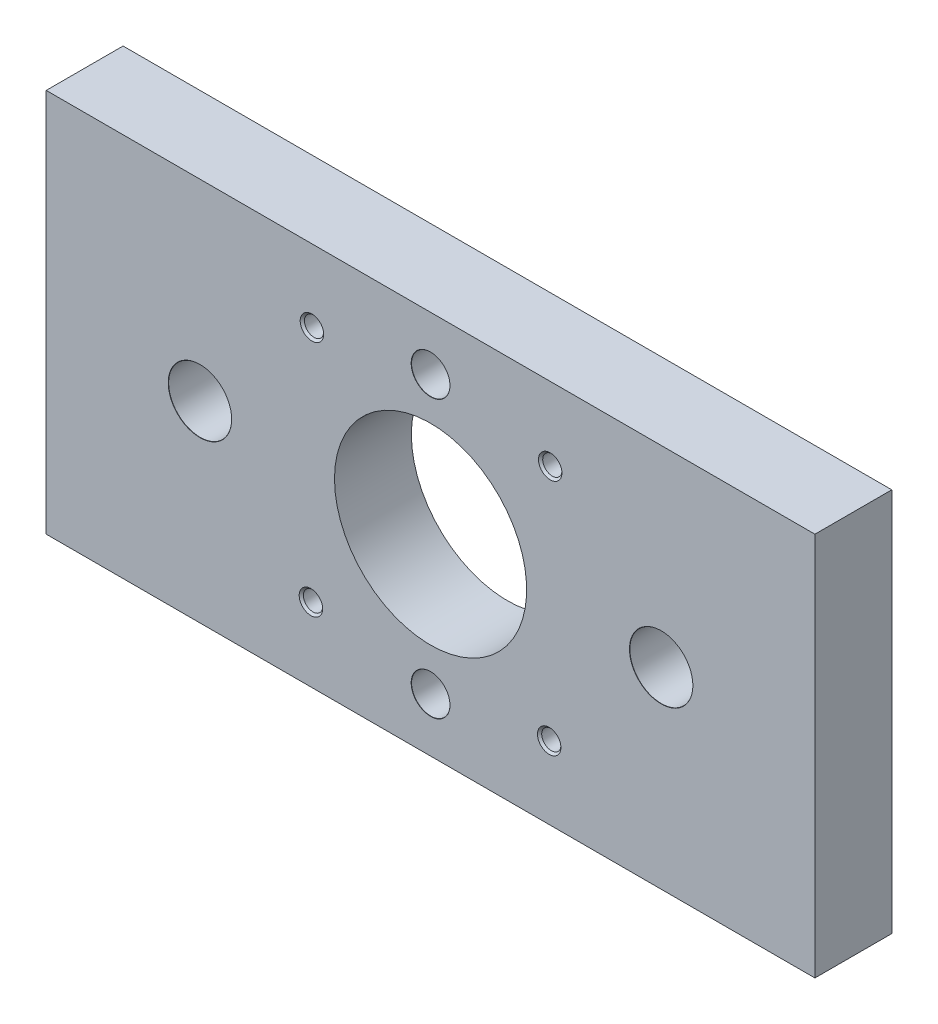
SolidWorks part; units mm, degrees
ref_plane "前视基准面" through (0, 0, 0) normal (0, 0, 1) x (1, 0, 0)
ref_plane "上视基准面" through (0, 0, 0) normal (0, 1, 0) x (1, 0, 0)
ref_plane "右视基准面" through (0, 0, 0) normal (1, 0, 0) x (0, 0, -1)
other "Configuration Table"
sketch "草图1" plane through (0, 0, 0) normal (0, 0, 1) x (1, 0, 0)
  line L1 (-50, -25) -> (50, -25)
  line L2 (-50, -25) -> (-50, 25)
  line L3 (-50, 25) -> (50, 25)
  line L4 (50, -25) -> (50, 25)
  line L5 (-50, -25) -> (50, 25) construction
  line L6 (-50, 25) -> (50, -25) construction
  point P0 (0, 0)
  dimension "D1" = 100
  dimension "D2" = 50
extrude "凸台-拉伸1" add sketch "草图1" along normal blind 10
ref_plane "基准面1" through (0, 0, 20) normal (0, 0, 1) x (1, 0, 0)
hole_wizard "Ø5.0 (5) 直径孔1" positions "草图12" profile "草图13" hole size "Ø5.0" standard "GB" end condition up to next
sketch "草图12" plane through (0, 0, 10) normal (0, 0, 1) x (1, 0, 0)
  line L0 (-50, 0) -> (50, 0) construction
  line L1 (-50, 25) -> (-50, -25) construction
  line L2 (50, -25) -> (50, 25) construction
  point P0 (0, 18)
  point P11 (0, -18)
  dimension "D1" = 18
sketch "草图13" plane through (0, 18, 10) normal (1, 0, 0) x (0, -1, 0)
  line L0 (0, 0) -> (0, 10)
  line L1 (0, 10) -> (2.5, 10)
  line L2 (2.5, 10) -> (2.5, 0.025)
  line L3 (2.5, 0.025) -> (2.525, 0)
  line L5 (2.525, 0) -> (0, 0)
  line L6 (-2.5, 0.025) -> (-2.525, 0) construction
  line L11 (0, -6.35) -> (0, 107.95) construction
  dimension "通孔孔直径" = 5
  dimension "通孔孔深度" = 10
  dimension "近端锥形沉头孔直径" = 5.05
  dimension "近端锥形沉头孔角度" = 90
ref_plane "基准面3" through (0, 0, 20) normal (0, 0, 1) x (1, 0, 0)
sketch "草图20" plane through (0, 0, 10) normal (0, 0, 1) x (1, 0, 0)
  circle A0 centre (0, 0) radius 5
  dimension "D1" = 10
extrude "切除-拉伸1" cut sketch "草图20" against normal through all contours A0
hole_wizard "Ø8.2 (8.2) 直径孔1" positions "草图24" profile "草图25" hole size "Ø8.2" standard "GB" end condition through all
sketch "草图24" plane through (0, 0, 10) normal (0, 0, 1) x (1, 0, 0)
  point P0 (30, 0)
  dimension "D1" = 30
sketch "草图25" plane through (30, 0, 10) normal (1, 0, 0) x (0, -1, 0)
  line L0 (0, 0) -> (0, 10)
  line L1 (0, 10) -> (4.125, 10)
  line L2 (4.1, 9.975) -> (4.1, 0.025)
  line L3 (4.1, 0.025) -> (4.125, 0)
  line L5 (4.125, 0) -> (0, 0)
  line L6 (-4.1, 0.025) -> (-4.125, 0) construction
  line L7 (4.125, 10) -> (4.1, 9.975)
  line L8 (-4.125, 10) -> (-4.1, 9.975) construction
  line L11 (0, -6.35) -> (0, 107.95) construction
  dimension "通孔孔直径" = 8.2
  dimension "通孔孔深度" = 10
  dimension "近端锥形沉头孔直径" = 8.25
  dimension "近端锥形沉头孔角度" = 90
  dimension "远端锥形沉头孔直径" = 8.25
  dimension "远端锥形沉头孔角度" = 90
ref_plane "基准面4" through (0, 0, 0) normal (1, 0, 0) x (0, 0, -1)
mirror "镜向1" about plane through (0, 0, 0) normal (1, 0, 0) of "Ø8.2 (8.2) 直径孔1"
sketch "草图26" plane through (0, 0, 0) normal (0, 0, -1) x (-1, 0, 0)
  circle A0 centre (0, 0) radius 12.5
  dimension "D1" = 25
extrude "切除-拉伸2" cut sketch "草图26" against normal blind 2.5
hole_wizard "M3 螺纹孔1" positions "草图29" profile "草图30" tap size "M3" standard "GB" end condition through all
sketch "草图29" plane through (0, 0, 10) normal (0, 0, 1) x (1, 0, 0)
  point P0 (15.5657, 15.434)
  point P3 (15.434, -15.5657)
  point P6 (-15.5657, -15.434)
  point P9 (-15.434, 15.5657)
sketch "草图30" plane through (15.5657, 15.434, 10) normal (1, 0, 0) x (0, -1, 0)
  line L0 (0, 0) -> (0, 10)
  line L1 (0, 10) -> (1.25, 10)
  line L2 (1.25, 10) -> (1.25, 0.275)
  line L3 (1.25, 0.275) -> (1.525, 0)
  line L5 (1.525, 0) -> (0, 0)
  line L6 (-1.25, 0.275) -> (-1.525, 0) construction
  line L11 (0, -6.35) -> (0, 107.95) construction
  dimension "通孔螺纹孔钻头直径" = 2.5
  dimension "通孔螺纹孔钻头深度" = 10
  dimension "近端锥形沉头孔直径" = 3.05
  dimension "近端锥形沉头孔角度" = 90
cosmetic thread "孔螺蚊线1" parameters "D2"=3
cosmetic thread "孔螺蚊线2" parameters "D2"=3
cosmetic thread "孔螺蚊线3" parameters "D2"=3
cosmetic thread "孔螺蚊线4" parameters "D2"=3
sketch "草图35" plane through (0, 0, 2.5) normal (0, 0, -1) x (-1, 0, 0)
  circle A0 centre (0, 0) radius 12.5
extrude "切除-拉伸3" cut sketch "草图35" against normal through all
